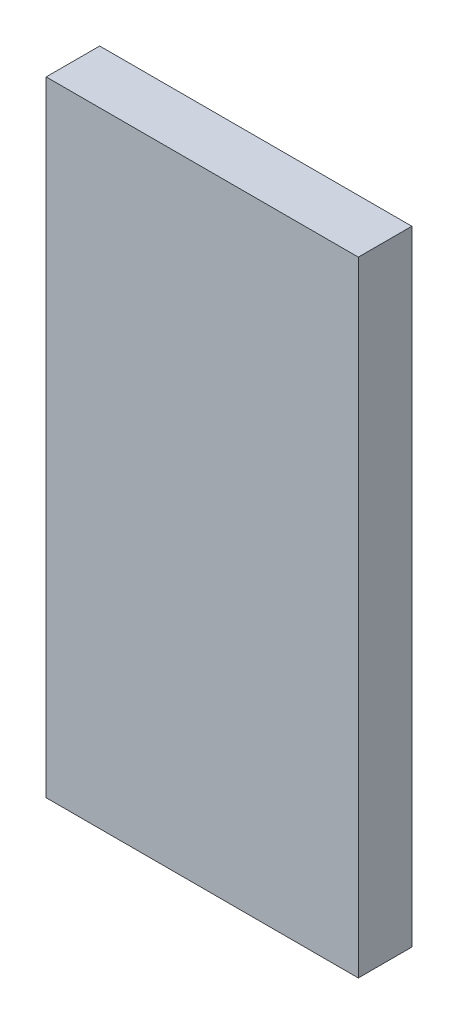
SolidWorks part; units mm, degrees
ref_plane "Front Plane" through (0, 0, 0) normal (0, 0, 1) x (1, 0, 0)
ref_plane "Top Plane" through (0, 0, 0) normal (0, 1, 0) x (1, 0, 0)
ref_plane "Right Plane" through (0, 0, 0) normal (1, 0, 0) x (0, 0, -1)
sketch "Sketch1" plane through (0, 0, 0) normal (0, 0, 1) x (1, 0, 0)
  line L1 (0, 0) -> (35, 0)
  line L2 (0, 0) -> (0, 70)
  line L3 (0, 70) -> (35, 70)
  line L4 (35, 0) -> (35, 70)
  dimension "D1" = 70
  dimension "D2" = 35
extrude "Boss-Extrude1" add sketch "Sketch1" along normal blind 6
